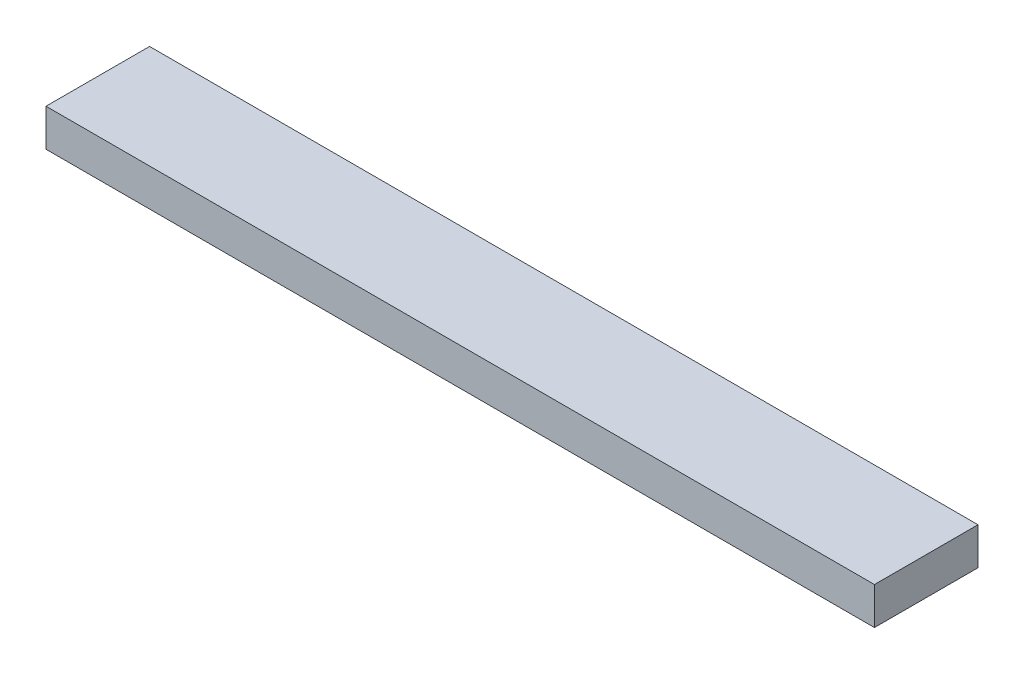
SolidWorks part; units mm, degrees
material "Perspex (TM) GS Acrylic Cast Sheet"
ref_plane "Front Plane" through (0, 0, 0) normal (0, 0, 1) x (1, 0, 0)
ref_plane "Top Plane" through (0, 0, 0) normal (0, 1, 0) x (1, 0, 0)
ref_plane "Right Plane" through (0, 0, 0) normal (1, 0, 0) x (0, 0, -1)
sketch "Sketch1" plane through (0, 0, 0) normal (0, 1, 0) x (1, 0, 0)
  line L1 (-50, -6.25) -> (50, -6.25)
  line L2 (-50, -6.25) -> (-50, 6.25)
  line L3 (-50, 6.25) -> (50, 6.25)
  line L4 (50, -6.25) -> (50, 6.25)
  line L5 (-50, -6.25) -> (50, 6.25) construction
  line L6 (-50, 6.25) -> (50, -6.25) construction
  point P0 (0, 0)
  point P5 (0, 0)
  dimension "D1" = 12.5
  dimension "D2" = 100
extrude "Boss-Extrude1" add sketch "Sketch1" along normal blind 4.5
